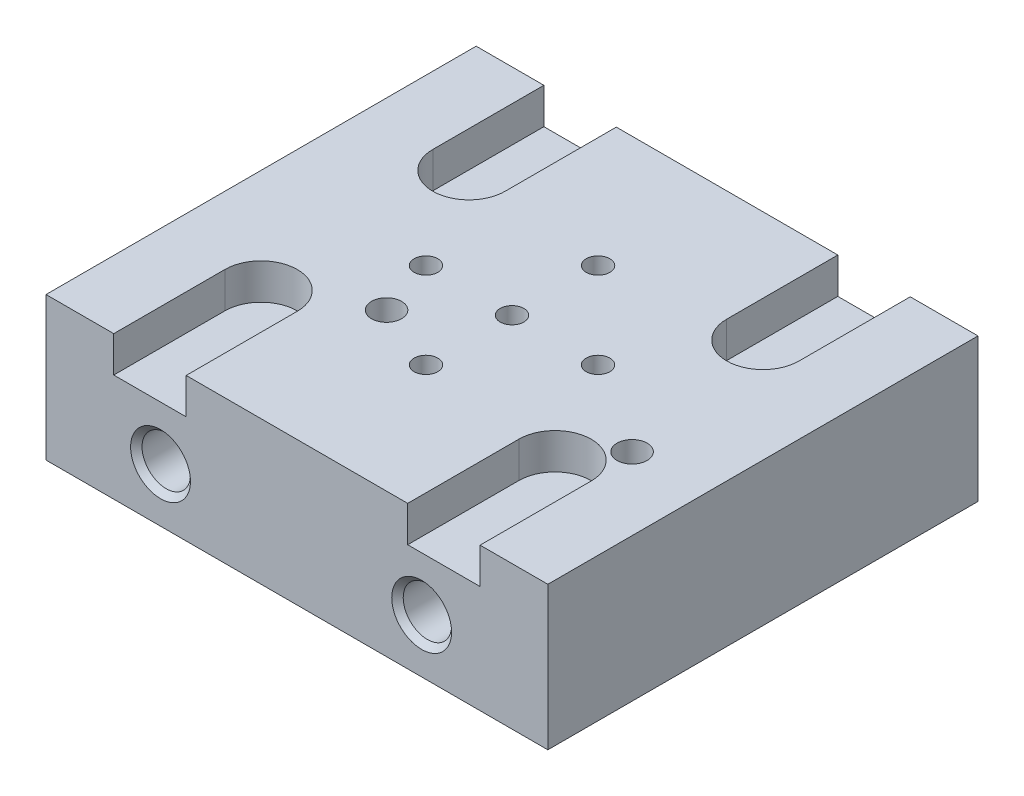
SolidWorks part; units mm, degrees
ref_plane "Front Plane" through (0, 0, 0) normal (0, 0, 1) x (1, 0, 0)
ref_plane "Top Plane" through (0, 0, 0) normal (0, 1, 0) x (1, 0, 0)
ref_plane "Right Plane" through (0, 0, 0) normal (1, 0, 0) x (0, 0, -1)
sketch "Sketch3" plane through (0, 0, 0) normal (0, 1, 0) x (1, 0, 0)
  line L1 (0, 0) -> (70, 0)
  line L2 (0, 0) -> (0, -60)
  line L3 (0, -60) -> (70, -60)
  line L4 (70, 0) -> (70, -60)
  dimension "D1" = 70
  dimension "D2" = 60
extrude "Boss-Extrude3" add sketch "Sketch3" along normal blind 20
sketch "Sketch4" plane through (0, 20, 0) normal (0, 1, 0) x (1, 0, 0)
  line L0 (35, 0) -> (35, -60) construction
  line L1 (70, 0) -> (0, 0) construction
  line L2 (0, -60) -> (70, -60) construction
  line L3 (0, -30) -> (70, -30) construction
  line L4 (0, 0) -> (0, -60) construction
  line L5 (70, -60) -> (70, 0) construction
  line L6 (21.35, -30) -> (21.35, 0) construction
  line L7 (0, 0) -> (70, 0) construction
  line L8 (24.65, -30) -> (24.65, 0) construction
  line L9 (45.35, -30) -> (45.35, 0) construction
  line L10 (48.65, -30) -> (48.65, 0) construction
  circle A0 centre (35, -30) radius 1.65
  circle A1 centre (35, -18) radius 1.65
  circle A2 centre (47, -30) radius 1.65
  circle A3 centre (35, -42) radius 1.65
  circle A4 centre (23, -30) radius 1.65
  dimension "D1" = 3.3
  dimension "D2" = 12
  dimension "D3" = 12
  dimension "D4" = 12
  dimension "D5" = 12
extrude "Cut-Extrude1" cut sketch "Sketch4" against normal through all
sketch "Sketch6" plane through (0, 0, 0) normal (0, -1, 0) x (1, 0, 0)
  line L0 (70, 30) -> (0, 30) construction
  line L1 (51.75, 21.875) -> (33.75, 21.875) construction
  line L2 (68, 21.875) -> (70, 21.875) construction
  line L3 (70, 60) -> (70, 0) construction
  line L4 (0, 0) -> (0, 60) construction
  line L5 (25.625, 21.875) -> (25.625, 0) construction
  line L6 (70, 0) -> (0, 0) construction
  line L7 (59.875, 21.875) -> (59.875, 0) construction
  line L8 (33.75, 21.875) -> (33.75, 0) construction
  line L9 (51.75, 21.875) -> (51.75, 0) construction
  line L10 (17.5, 21.875) -> (17.5, 0) construction
  line L11 (68, 21.875) -> (68, 0) construction
  line L12 (57.775, 21.875) -> (57.775, 0) construction
  line L13 (61.975, 21.875) -> (61.975, 0) construction
  line L14 (27.725, 21.875) -> (27.725, 0) construction
  line L15 (23.525, 21.875) -> (23.525, 0) construction
  line L16 (34.9322, 43.6486) -> (34.9322, 60) construction
  line L17 (34.9322, 16.3514) -> (34.9322, 0) construction
  line L18 (23.525, 38.125) -> (23.525, 60) construction
  line L19 (27.725, 38.125) -> (27.725, 60) construction
  line L20 (61.975, 38.125) -> (61.975, 60) construction
  line L21 (57.775, 38.125) -> (57.775, 60) construction
  line L22 (68, 38.125) -> (68, 60) construction
  line L23 (17.5, 38.125) -> (17.5, 60) construction
  line L24 (51.75, 38.125) -> (51.75, 60) construction
  line L25 (33.75, 38.125) -> (33.75, 60) construction
  line L26 (59.875, 38.125) -> (59.875, 60) construction
  line L27 (25.625, 38.125) -> (25.625, 60) construction
  line L28 (68, 38.125) -> (70, 38.125) construction
  line L29 (51.75, 38.125) -> (33.75, 38.125) construction
  circle A2 centre (59.875, 21.875) radius 8.125 construction
  circle A3 centre (25.625, 21.875) radius 8.125 construction
  circle A4 centre (59.875, 21.875) radius 2.1
  circle A5 centre (25.625, 21.875) radius 2.1
  circle A6 centre (35, 18) radius 1.65 construction
  circle A7 centre (25.625, 38.125) radius 8.125 construction
  circle A8 centre (59.875, 38.125) radius 8.125 construction
  circle A9 centre (25.625, 38.125) radius 2.1
  circle A10 centre (59.875, 38.125) radius 2.1
  dimension "D1" = 16.25
  dimension "D2" = 18
  dimension "D3" = 4.2
  dimension "D4" = 2
extrude "Cut-Extrude2" cut sketch "Sketch6" against normal through all contours A9 | A10 | A5
sketch "Sketch9" plane through (0, 0, 60) normal (0, 0, -1) x (-1, 0, 0)
  line L0 (-25.625, 0) -> (-25.625, 20) construction
  line L1 (-70, 20) -> (0, 20) construction
  line L2 (-59.875, 0) -> (-59.875, 20) construction
  line L3 (-68, 0) -> (-51.75, 0) construction
  line L4 (-17.5, 0) -> (-17.5, 20) construction
  line L5 (-33.75, 0) -> (-33.75, 20) construction
  line L6 (-51.75, 0) -> (-51.75, 20) construction
  line L7 (-68, 0) -> (-68, 20) construction
  line L8 (-57.775, 0) -> (-57.775, 20) construction
  line L9 (-61.975, 0) -> (-61.975, 20) construction
  line L10 (-27.725, 0) -> (-27.725, 20) construction
  line L11 (-23.525, 0) -> (-23.525, 20) construction
  line L12 (-57.775, 7.5) -> (-55.775, 7.5) construction
  line L13 (-52.4, 10.875) -> (-52.4, 20) construction
  line L14 (-12.6, 7.5) -> (0, 7.5) construction
  line L15 (-19.35, 7.5) -> (-21.35, 7.5) construction
  line L16 (-15.975, 20) -> (-15.975, 10.875) construction
  line L17 (0, 20) -> (0, 0) construction
  line L18 (-34.9322, 0) -> (-34.9322, 20) construction
  line L19 (-34.9322, 0) -> (-34.9322, 20) construction
  line L20 (-49.025, 7.5) -> (-34.9322, 7.5) construction
  line L21 (-21.35, 20) -> (-21.35, 0) construction
  line L22 (0, 0) -> (-70, 0) construction
  line L23 (-24.65, 20) -> (-24.65, 0) construction
  line L24 (-45.35, 20) -> (-45.35, 0) construction
  line L25 (-48.65, 20) -> (-48.65, 0) construction
  line L26 (0, 7.5) -> (0, 20) construction
  circle A0 centre (-52.4, 7.5) radius 3.375
  circle A1 centre (-15.975, 7.5) radius 3.375
  dimension "D1" = 6.75
  dimension "D2" = 2
  dimension "D3" = 2
  dimension "D4" = 12.5
extrude "Cut-Extrude3" cut sketch "Sketch9" along normal blind 40.25
sketch "Sketch11" plane through (0, 0, 0) normal (0, -1, 0) x (1, 0, 0)
  line L0 (70, 30) -> (0, 30) construction
  circle A0 centre (23, 30) radius 3
  circle A1 centre (35, 42) radius 3
  circle A2 centre (35, 30) radius 3
  circle A3 centre (35, 18) radius 3
  circle A4 centre (47, 30) radius 3
  circle M3 centre (35, 18) radius 1.65
  circle M4 centre (47, 30) radius 1.65
  circle M5 centre (35, 42) radius 1.65
  circle M6 centre (23, 30) radius 1.65
  circle M7 centre (35, 30) radius 1.65
  dimension "D1" = 6
extrude "Cut-Extrude4" cut sketch "Sketch11" against normal blind 3 contours A3 M3 | A2 M7 | A4 M4 | A0 M6 | A1 M5 | M5 | M6 | M7 | M4 | M3
sketch "Sketch12" plane through (0, 20, 0) normal (0, 1, 0) x (1, 0, 0)
  line L0 (35, -60.1049) -> (14.5, -60.1049) construction
  line L1 (35, 0.1049) -> (35, -60.1049) construction
  line L2 (14.5, -60.1049) -> (14.5, -44.5) construction
  line L3 (9.45, -60.1049) -> (9.45, -44.5)
  line L4 (19.55, -60.1049) -> (19.55, -44.5)
  line L5 (70, -30) -> (0, -30) construction
  line L6 (35, 0) -> (35, -60) construction
  line L7 (35, 0.1049) -> (14.5, 0.1049) construction
  line L8 (55.5, -60.1049) -> (55.5, -44.5) construction
  line L9 (60.55, -60.1049) -> (60.55, -44.5)
  line L10 (50.45, -60.1049) -> (50.45, -44.5)
  line L11 (55.5, 0.1049) -> (55.5, -15.5) construction
  line L12 (60.55, 0.1049) -> (60.55, -15.5)
  line L13 (50.45, 0.1049) -> (50.45, -15.5)
  line L14 (14.5, 0.1049) -> (14.5, -15.5) construction
  line L15 (9.45, 0.1049) -> (9.45, -15.5)
  line L16 (19.55, 0.1049) -> (19.55, -15.5)
  arc A0 (9.45, -60.1049) -> (19.55, -60.1049) centre (14.5, -60.1049) ccw
  arc A1 (19.55, -44.5) -> (9.45, -44.5) centre (14.5, -44.5) ccw
  arc A3 (60.55, -60.1049) -> (50.45, -60.1049) centre (55.5, -60.1049) cw
  arc A4 (50.45, -44.5) -> (60.55, -44.5) centre (55.5, -44.5) cw
  arc A6 (60.55, 0.1049) -> (50.45, 0.1049) centre (55.5, 0.1049) ccw
  arc A7 (50.45, -15.5) -> (60.55, -15.5) centre (55.5, -15.5) ccw
  arc A8 (9.45, 0.1049) -> (19.55, 0.1049) centre (14.5, 0.1049) cw
  arc A9 (19.55, -15.5) -> (9.45, -15.5) centre (14.5, -15.5) cw
  point P0 (14.5, -52.3025)
  point P19 (35, -30)
  point P23 (55.5, -52.3025)
  point P29 (55.5, -7.6975)
  point P36 (14.5, -7.6975)
  dimension "D4" = 5.05
  dimension "D1" = 20.5
extrude "Cut-Extrude5" cut sketch "Sketch12" against normal blind 5
chamfer "Chamfer2" distance 0.8 angle 45 2 edges at (12.6, 7.5, 60) (49.025, 7.5, 60)
